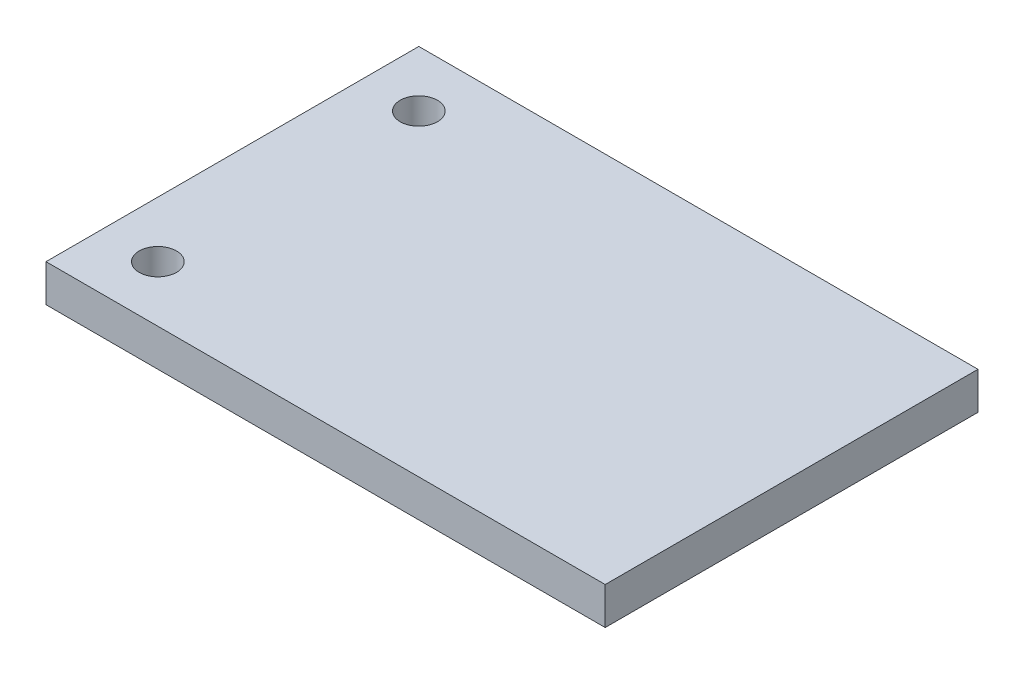
SolidWorks part; units mm, degrees
ref_plane "Płaszczyzna przednia" through (0, 0, 0) normal (0, 0, 1) x (1, 0, 0)
ref_plane "Płaszczyzna górna" through (0, 0, 0) normal (0, 1, 0) x (1, 0, 0)
ref_plane "Płaszczyzna prawa" through (0, 0, 0) normal (1, 0, 0) x (0, 0, -1)
sketch "Szkic1" plane through (0, 0, 0) normal (0, 1, 0) x (1, 0, 0)
  line L1 (0, 0) -> (300, 0)
  line L2 (0, 0) -> (0, 200)
  line L3 (0, 200) -> (300, 200)
  line L4 (300, 0) -> (300, 200)
  circle A0 centre (30, 30) radius 10
  circle A1 centre (30, 170) radius 10
  dimension "D3" = 20
  dimension "D4" = 20
  dimension "D1" = 200
  dimension "D2" = 300
  dimension "D5" = 30
  dimension "D6" = 30
  dimension "D7" = 30
extrude "Dodanie-wyciągnięcie1" add sketch "Szkic1" along normal blind 20
other "Grafika1" [suppressed]
other "Grafika (Zamknięta) -1"
sketch "Szkic2" [suppressed] plane through (0, 0, 0) normal (0, 1, 0) x (1, 0, 0)
  line L0 (0, 200.1688) -> (299.8741, 200.1688)
  line L1 (299.8741, 200.1688) -> (299.8741, 185.2745)
  line L2 (299.8741, 185.2745) -> (287.3517, 185.5584)
  line L3 (287.3517, 185.5584) -> (176.4906, 78.1321)
  line L4 (176.4906, 78.1321) -> (61.7555, 12.725)
  line L5 (15.6408, 45.4286) -> (33.831, 53.8336)
  line L6 (33.831, 53.8336) -> (92.6298, 101.448)
  line L7 (92.6298, 118.5603) -> (50.7167, 142.8825)
  line L8 (0, 181.1044) -> (0, 200.1688)
  line L9 (8.4025, 181.1044) -> (0, 181.1044)
  arc A0 (61.7555, 12.725) -> (10.3657, 22.9885) centre (41.968, 47.4356) cw
  arc A1 (10.3657, 22.9885) -> (15.6408, 45.4286) centre (22.1041, 32.0691) cw
  arc A2 (92.6298, 101.448) -> (92.6298, 118.5603) centre (85.7012, 110.0042) ccw
  arc A3 (50.7167, 142.8825) -> (27.5887, 149.107) centre (27.5887, 103.027) ccw
  arc A4 (27.5887, 149.107) -> (7.6572, 173.1729) centre (27.5887, 169.3936) cw
  arc A5 (7.6572, 173.1729) -> (8.4025, 181.1044) centre (-34.173, 181.1044) ccw
  circle A6 centre (29.9604, 169.3936) radius 8.718
  circle A7 centre (29.9604, 30.2638) radius 8.8738
extrude "Dodanie-wyciągnięcie2" [suppressed] add sketch "Szkic2" along normal blind 20
